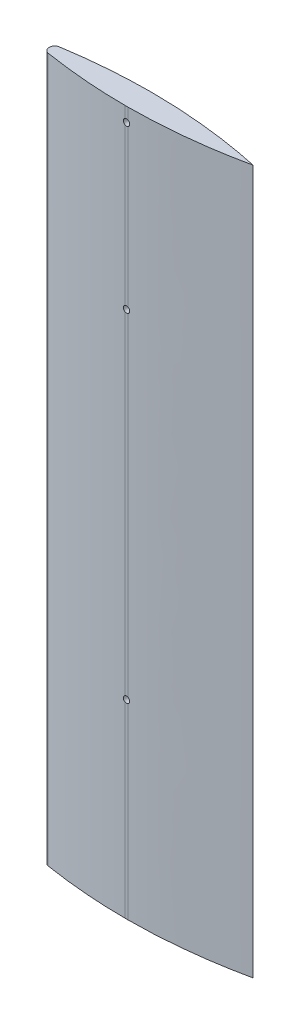
SolidWorks part; units mm, degrees
ref_plane "Plan de face" through (0, 0, 0) normal (0, 0, 1) x (1, 0, 0)
ref_plane "Plan de dessus" through (0, 0, 0) normal (0, 1, 0) x (1, 0, 0)
ref_plane "Plan de droite" through (0, 0, 0) normal (1, 0, 0) x (0, 0, -1)
sketch "Esquisse1" plane through (0, 0, 0) normal (0, 1, 0) x (1, 0, 0)
  line L0 (-19.4444, 17.5) -> (-19.4444, -17.5)
  line L1 (145, 17.5) -> (-145, 17.5)
  line L2 (145, 17.5) -> (145, -17.5)
  line L3 (145, -17.5) -> (-145, -17.5)
  line L4 (-145, 17.5) -> (-145, -17.5)
  line L5 (145, 17.5) -> (-145, -17.5) construction
  line L6 (145, -17.5) -> (-145, 17.5) construction
  line L7 (-19.4444, -35.4999) -> (-142.0933, -7.0304)
  line L8 (-138.6429, 0) -> (-138.6429, 7.8313)
  line L9 (-19.4444, 17.5) -> (-19.4444, 35.5001)
  line L10 (-19.4444, -17.5) -> (-19.4444, -35.4999)
  line L11 (-19.4444, 35.5001) -> (-146.6533, 5.972)
  line L12 (-138.6429, 0) -> (-138.6429, -7.8313)
  line L13 (-145, 0) -> (-137, 0)
  circle A0 centre (-137, 0) radius 8
  spline S0 degree 2 poles (-138.6429, 7.8313) (3.5122, 30.5127) (145, 0) knots 0 0 0 1 1 1
  spline S1 degree 2 poles (-138.6429, -7.8313) (3.5122, -30.5127) (145, 0) knots 0 0 0 1 1 1
  point P0 (0, 0)
extrude "Boss.-Extru.1" add sketch "Esquisse1" along normal blind 1000
hole_wizard "Dégagement M81" positions "Esquisse3D1" profile "Esquisse2" hole size "M8" standard "ISO"
sketch3d "Esquisse3D1"
  line L0 (-15.6308, 1000, 17.5) -> (-15.6308, 0, 17.5) construction
  point P0 (-15.6308, 16.7628, 17.5)
  point P4 (-15.6308, 500, 17.5)
  point P6 (-15.6308, 987.8527, 17.5)
  point P9 (-17.5, 270, 17.5)
  point P11 (-17.5, 750, 17.5)
  point P13 (-17.5, 980, 17.5)
sketch "Esquisse2" plane through (-17.5, 270, 17.5) normal (1, 0, 0) x (0, -1, 0)
  line L0 (0, 0) -> (0, 35)
  line L1 (0, 35) -> (4.5, 35)
  line L2 (4.5, 35) -> (4.5, 0)
  line L5 (4.5, 0) -> (0, 0)
  line L11 (0, -6.35) -> (0, 107.95) construction
  dimension "Diamètre du perçage jusqu'au prochain" = 9
  dimension "Profondeur du perçage jusqu'au prochain" = 35
